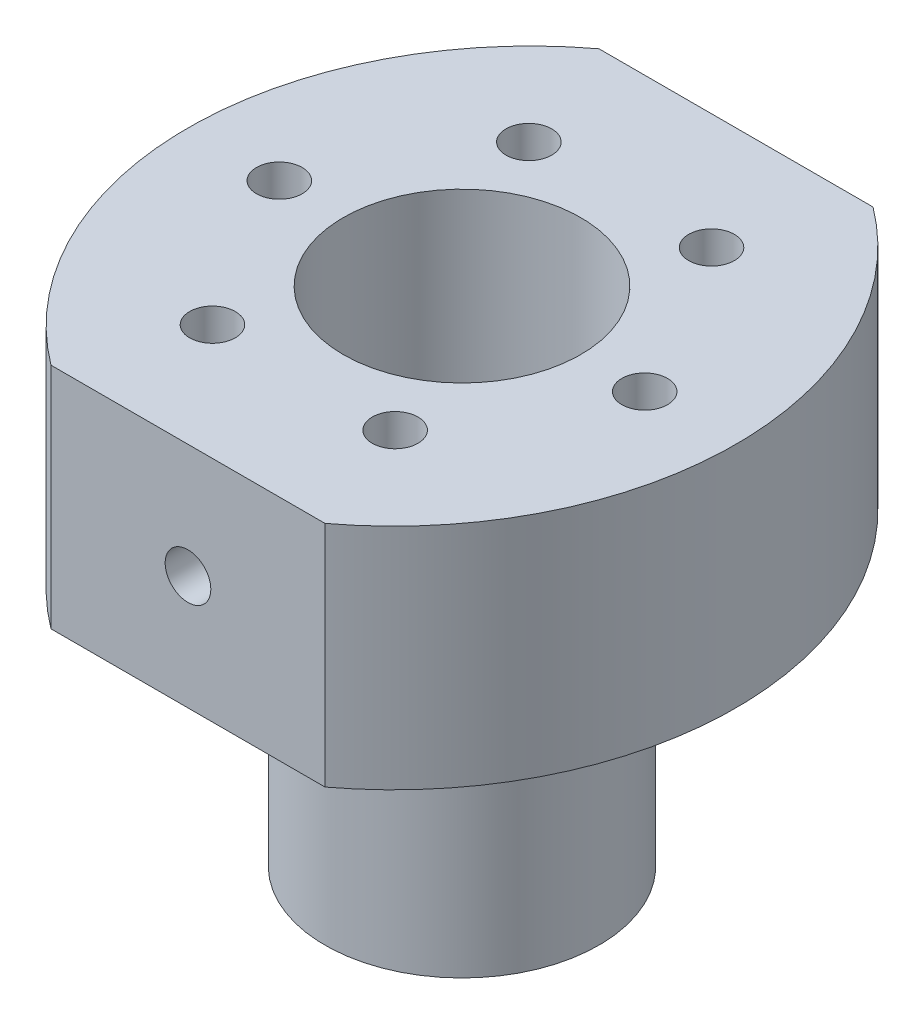
SolidWorks part; units mm, degrees
material "Acero al carbono no aleado"
ref_plane "Alzado" through (0, 0, 0) normal (0, 0, 1) x (1, 0, 0)
ref_plane "Planta" through (0, 0, 0) normal (0, 1, 0) x (1, 0, 0)
ref_plane "Vista lateral" through (0, 0, 0) normal (1, 0, 0) x (0, 0, -1)
sketch "Croquis1" plane through (0, 0, 0) normal (0, 1, 0) x (1, 0, 0)
  line L0 (-15, -30) -> (15, -30)
  line L11 (-15, 30) -> (15, 30)
  circle A0 centre (0, 0) radius 30 construction
  arc A2 (-15, 30) -> (-15, -30) centre (7.5, 0) ccw
  arc A3 (15, 30) -> (15, -30) centre (-7.5, 0) cw
  point P8 (-15, 30)
  point P9 (15, 30)
  dimension "D1" = 60
  dimension "D2" = 30
extrude "Saliente-Extruir2" add sketch "Croquis1" along normal mid plane 25
sketch "Croquis31" plane through (0, -12.5, 0) normal (0, -1, 0) x (-1, 0, 0)
  circle A0 centre (0, 0) radius 15
  dimension "D1" = 30
extrude "Saliente-Extruir3" add sketch "Croquis31" along normal blind 30 contours A0
sketch "Croquis8" plane through (0, 12.5, 0) normal (0, 1, 0) x (1, 0, 0)
  circle A0 centre (0, 0) radius 13
  dimension "D1" = 26
extrude "Cortar-Extruir2" cut sketch "Croquis8" against normal blind 100
sketch "Croquis33" plane through (0, 0, -30) normal (0, 0, -1) x (-1, 0, 0)
  circle A0 centre (0, 0) radius 2.5
  dimension "D1" = 5
extrude "Cortar-Extruir9" cut sketch "Croquis33" against normal mid plane 5
sketch "Croquis34" plane through (0, 0, 30) normal (0, 0, 1) x (1, 0, 0)
  circle A0 centre (0, 0) radius 2.5
  dimension "D1" = 5
extrude "Cortar-Extruir10" cut sketch "Croquis34" against normal blind 5
sketch "Croquis35" plane through (0, 12.5, 0) normal (0, 1, 0) x (1, 0, 0)
  line L0 (0, 0) -> (-20, 0) construction
  line L1 (0, 0) -> (-10, 17.3205) construction
  circle A0 centre (20, 0) radius 2.5
  circle A1 centre (-20, 0) radius 2.5
  circle A2 centre (-10, 17.3205) radius 2.5
  circle A3 centre (10, 17.3205) radius 2.5
  circle A4 centre (20, 0) radius 2.5
  circle A5 centre (10, -17.3205) radius 2.5
  circle A6 centre (-10, -17.3205) radius 2.5
  dimension "D3" = 5
  dimension "D4" = 5
  dimension "D1" = 20
  dimension "D2" = 20
  dimension "D6" = 60
  dimension "D5" = 6
extrude "Cortar-Extruir11" cut sketch "Croquis35" against normal blind 25 contours A3 | A2 | A1 | A6 | A5 | A0
